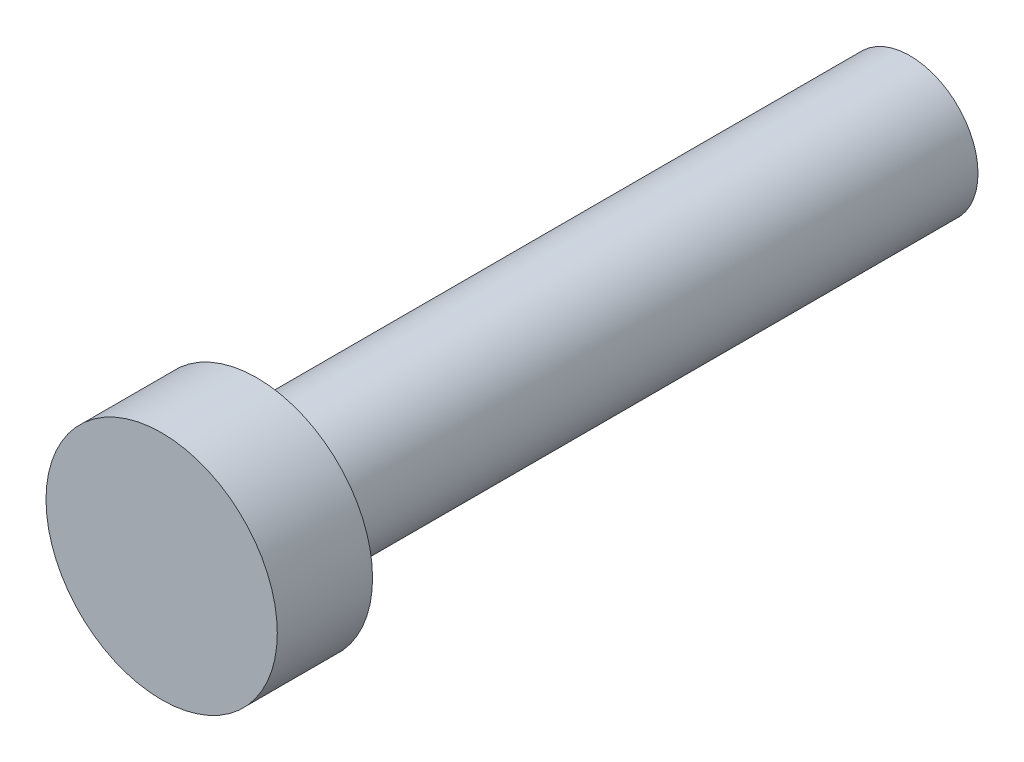
SolidWorks part; units mm, degrees
ref_plane "Front Plane" through (0, 0, 0) normal (0, 0, 1) x (1, 0, 0)
ref_plane "Top Plane" through (0, 0, 0) normal (0, 1, 0) x (1, 0, 0)
ref_plane "Right Plane" through (0, 0, 0) normal (1, 0, 0) x (0, 0, -1)
ref_plane "Plane1" through (0, 0, 338.5) normal (0, 0, 1) x (1, 0, 0)
sketch "Sketch1" plane through (0, 0, 338.5) normal (0, 0, 1) x (1, 0, 0)
  circle A0 centre (300, 40) radius 2.5
extrude "Boss-Extrude1" add sketch "Sketch1" along normal blind 24
ref_plane "Plane2" through (0, 0, 362.5) normal (0, 0, 1) x (1, 0, 0)
sketch "Sketch2" plane through (0, 0, 362.5) normal (0, 0, 1) x (1, 0, 0)
  circle A0 centre (300, 40) radius 4.25
extrude "Boss-Extrude2" add sketch "Sketch2" along normal blind 3.5
